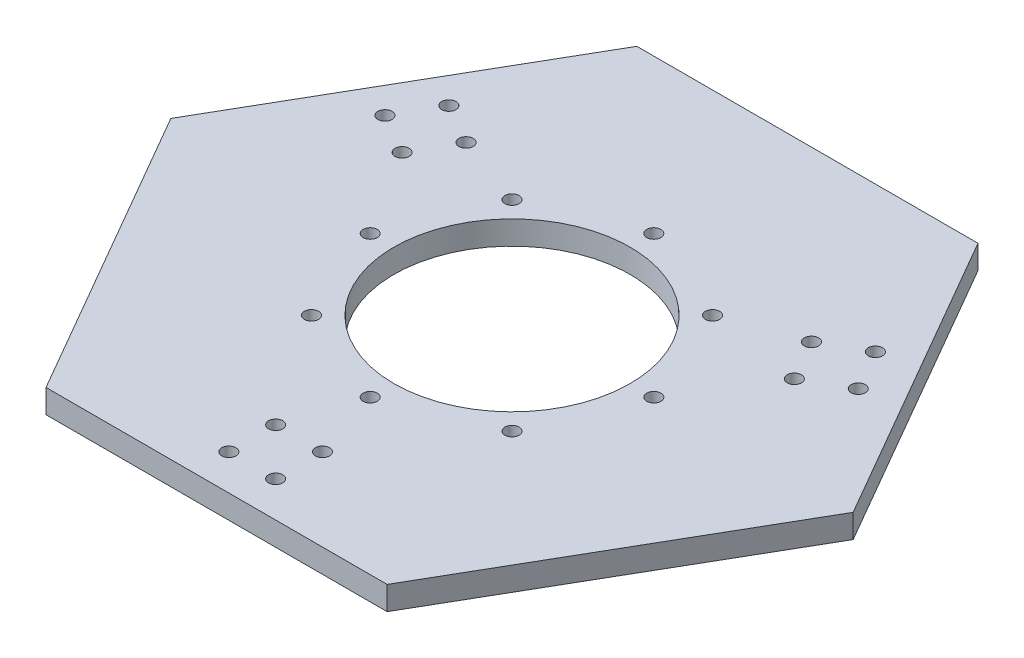
SolidWorks part; units mm, degrees
ref_plane "前视基准面" through (0, 0, 0) normal (0, 0, 1) x (1, 0, 0)
ref_plane "上视基准面" through (0, 0, 0) normal (0, 1, 0) x (1, 0, 0)
ref_plane "右视基准面" through (0, 0, 0) normal (1, 0, 0) x (0, 0, -1)
other "Configuration Table"
sketch "草图1" plane through (0, 0, 0) normal (0, 1, 0) x (1, 0, 0)
  line L1 (36.0844, 62.5) -> (-36.0844, 62.5)
  line L2 (-36.0844, 62.5) -> (-72.1688, 0)
  line L3 (-72.1688, 0) -> (-36.0844, -62.5)
  line L4 (-36.0844, -62.5) -> (36.0844, -62.5)
  line L5 (36.0844, -62.5) -> (72.1688, 0)
  line L6 (72.1688, 0) -> (36.0844, 62.5)
  circle A0 centre (0, 0) radius 62.5 construction
  dimension "D1" = 125
extrude "凸台-拉伸1" add sketch "草图1" along normal blind 5
sketch "草图2" plane through (0, 5, 0) normal (0, 1, 0) x (1, 0, 0)
  circle A0 centre (0, 0) radius 25
  dimension "D1" = 50
extrude "切除-拉伸1" cut sketch "草图2" against normal blind 5
sketch "草图3" plane through (0, 5, 0) normal (0, 1, 0) x (1, 0, 0)
  line L0 (0, -50) -> (0, 0) construction
  line L1 (-4.95, -54.95) -> (4.95, -54.95) construction
  line L2 (-4.95, -54.95) -> (-4.95, -45.05) construction
  line L3 (-4.95, -45.05) -> (4.95, -45.05) construction
  line L4 (4.95, -54.95) -> (4.95, -45.05) construction
  line L5 (-4.95, -54.95) -> (4.95, -45.05) construction
  line L6 (-4.95, -45.05) -> (4.95, -54.95) construction
  circle A0 centre (0, 0) radius 50 construction
  circle A1 centre (-4.95, -45.05) radius 1.5
  circle A2 centre (4.95, -45.05) radius 1.5
  circle A3 centre (-4.95, -54.95) radius 1.5
  circle A4 centre (4.95, -54.95) radius 1.5
  point P3 (0, -50)
  dimension "D1" = 100
  dimension "D4" = 3
  dimension "D5" = 3
  dimension "D6" = 3
  dimension "D7" = 3
  dimension "D2" = 9.9
  dimension "D3" = 9.9
extrude "切除-拉伸2" cut sketch "草图3" against normal blind 5
pattern_circular "阵列(圆周)1" count 3 over 360 about axis through (0, 0, 0) along (0, 1, 0) of "切除-拉伸2"
sketch "草图5" plane through (0, 0, 0) normal (0, -1, 0) x (1, 0, 0)
  circle A0 centre (0, 30) radius 1.5
extrude "切除-拉伸3" cut sketch "草图5" against normal blind 13
pattern_circular "阵列(圆周)2" count 8 over 360 about axis through (0, 0, 0) along (0, 1, 0) of "切除-拉伸3"
